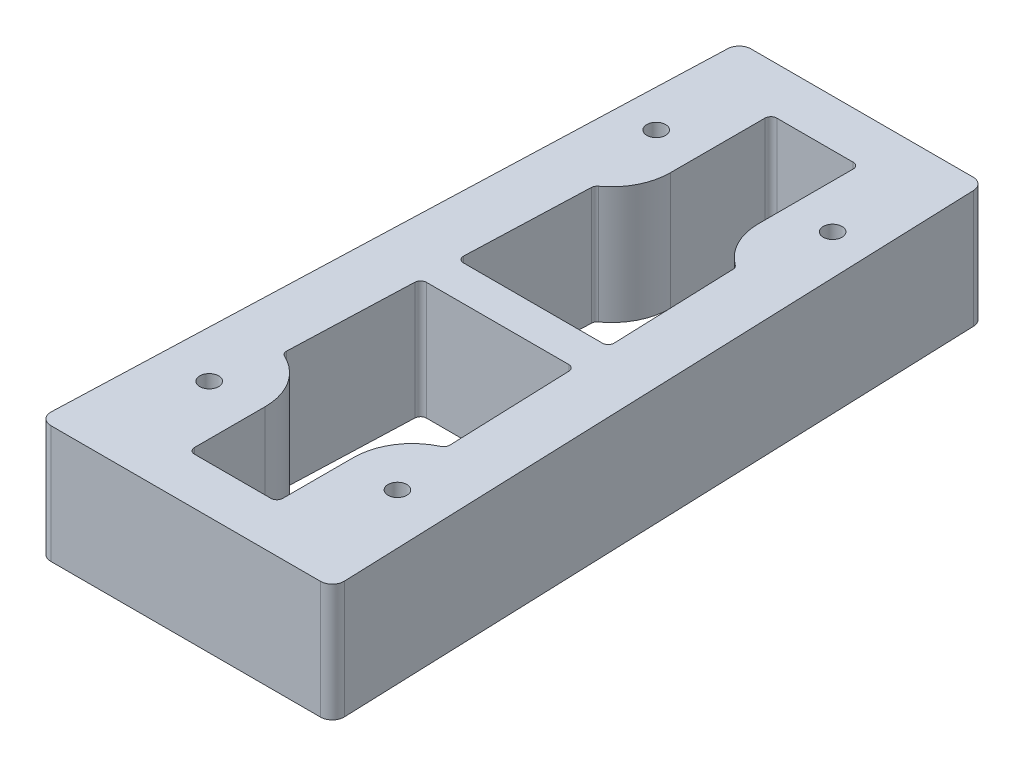
SolidWorks part; units mm, degrees
material "ABS"
ref_plane "前视基准面" through (0, 0, 0) normal (0, 0, 1) x (1, 0, 0)
ref_plane "上视基准面" through (0, 0, 0) normal (0, 1, 0) x (1, 0, 0)
ref_plane "右视基准面" through (0, 0, 0) normal (1, 0, 0) x (0, 0, -1)
other "Configuration Table"
sketch "草图1" plane through (0, 0, 0) normal (0, 1, 0) x (1, 0, 0)
  line L0 (-25, 0) -> (-19, 0)
  line L1 (-19, 165) -> (19, 165)
  line L2 (-19, 165) -> (-19, 0)
  line L3 (-19, 0) -> (19, 0) construction
  line L4 (19, 165) -> (19, 0)
  line L5 (-25, 0) -> (25, 0) construction
  line L6 (-25, 0) -> (-25, -15)
  line L7 (-25, -15) -> (25, -15)
  line L8 (25, 0) -> (25, -15)
  line L9 (19, 0) -> (25, 0)
  line L10 (-19, 156) -> (19, 156) construction
  line L11 (-25, -7.5) -> (25, -7.5) construction
  circle A0 centre (0, -7.5) radius 1.6
  circle A1 centre (20, -7.5) radius 1.6
  circle A2 centre (-20, -7.5) radius 1.6
  circle A3 centre (-15, 156) radius 2.1
  circle A4 centre (15, 156) radius 2.1
  point P8 (22, 0)
  dimension "D7" = 3.2
  dimension "D8" = 3.2
  dimension "D9" = 3.2
  dimension "D12" = 4.2
  dimension "D13" = 4.2
  dimension "D1" = 15
  dimension "D2" = 38
  dimension "D3" = 50
  dimension "D4" = 25
  dimension "D5" = 165
  dimension "D6" = 156
  dimension "D10" = 20
  dimension "D11" = 20
  dimension "D14" = 15
  dimension "D15" = 30
extrude "凸台-拉伸1" add sketch "草图1" along normal blind 20
sketch "草图2" plane through (0, 20, 0) normal (0, 1, 0) x (1, 0, 0)
  line L0 (-19, 165) -> (-25, 0)
  line L1 (-25, 0) -> (-19, 0)
  line L2 (-19, 0) -> (-19, 165)
  line L3 (19, 165) -> (25, 0)
  line L4 (25, 0) -> (19, 0)
  line L5 (19, 0) -> (19, 165)
extrude "凸台-拉伸2" add sketch "草图2" against normal blind 20
sketch "草图3" plane through (0, 20, 0) normal (0, 1, 0) x (1, 0, 0)
  line L0 (-16, 20) -> (16, 20) construction
  line L1 (0, 20) -> (0, 0) construction
  circle A0 centre (16, 20) radius 1.6
  circle A1 centre (-16, 20) radius 1.6
  dimension "D1" = 3.2
  dimension "D2" = 3.2
  dimension "D3" = 32
  dimension "D4" = 20
extrude "切除-拉伸1" cut sketch "草图3" against normal through all
sketch "草图4" plane through (0, 20, 0) normal (0, 1, 0) x (1, 0, 0)
  line L0 (0, 95) -> (0, 0) construction
  line L1 (-15, 95) -> (15, 95) construction
  circle A0 centre (-15, 95) radius 1.6
  circle A1 centre (15, 95) radius 1.6
  dimension "D2" = 3.2
  dimension "D3" = 3.2
  dimension "D1" = 95
  dimension "D4" = 30
extrude "切除-拉伸2" cut sketch "草图4" against normal through all
sketch "草图6" plane through (0, 20, 0) normal (0, 1, 0) x (1, 0, 0)
  line L1 (-25, -15) -> (25, -15)
  line L2 (-25, -15) -> (-25, 0)
  line L3 (-25, 0) -> (25, 0)
  line L4 (25, -15) -> (25, 0)
  line L5 (-39.8866, 115) -> (37.9308, 115)
  line L6 (-39.8866, 115) -> (-39.8866, 196.5424)
  line L7 (-39.8866, 196.5424) -> (37.9308, 196.5424)
  line L8 (37.9308, 115) -> (37.9308, 196.5424)
  point P10 (37.9308, 176.5424)
  dimension "D1" = 115
extrude "切除-拉伸3" cut sketch "草图6" against normal through all
fillet "圆角1" radius 2 4 edges at (-25, 10, 0) (25, 10, 0) (20.8182, 10, -115) (-20.8182, 10, -115)
sketch "草图7" plane through (0, 0, 0) normal (0, -1, 0) x (1, 0, 0)
  line L1 (-13.9025, -30) -> (-12.0116, -82)
  line L3 (12.0116, -82) -> (13.9025, -30)
  line L4 (22.926, 0) -> (-22.926, 0)
  line L5 (-24.9246, -2.0727) -> (-20.8883, -113.0727)
  line L6 (-18.8896, -115) -> (18.8896, -115)
  line L7 (20.8883, -113.0727) -> (24.9246, -2.0727)
  line L8 (22.926, 0) -> (-22.926, 0)
  line L9 (-24.9246, -2.0727) -> (-20.8883, -113.0727)
  line L10 (-18.8896, -115) -> (18.8896, -115)
  line L11 (20.8883, -113.0727) -> (24.9246, -2.0727)
  line L12 (-13.9025, -30) -> (13.9025, -30)
  line L13 (-12.0116, -82) -> (12.0116, -82)
  line L14 (-14.6298, -10) -> (-11.1752, -105) construction
  line L15 (-11.1752, -105) -> (11.1752, -105) construction
  line L16 (11.1752, -105) -> (14.6298, -10) construction
  line L17 (14.6298, -10) -> (-14.6298, -10) construction
  arc A0 (-14.6298, -10) -> (-14.6298, -10) centre (-14.6298, -10) ccw
  arc A1 (-11.1752, -105) -> (-11.1752, -105) centre (-11.1752, -105) ccw
  arc A2 (11.1752, -105) -> (11.1752, -105) centre (11.1752, -105) ccw
  arc A3 (14.6298, -10) -> (14.6298, -10) centre (14.6298, -10) ccw
  arc A4 (-22.926, 0) -> (-24.9246, -2.0727) centre (-22.926, -2) ccw
  arc A5 (-20.8883, -113.0727) -> (-18.8896, -115) centre (-18.8896, -113) ccw
  arc A6 (18.8896, -115) -> (20.8883, -113.0727) centre (18.8896, -113) ccw
  arc A7 (24.9246, -2.0727) -> (22.926, 0) centre (22.926, -2) ccw
  arc A8 (-22.926, 0) -> (-24.9246, -2.0727) centre (-22.926, -2) ccw
  arc A9 (-20.8883, -113.0727) -> (-18.8896, -115) centre (-18.8896, -113) ccw
  arc A10 (18.8896, -115) -> (20.8883, -113.0727) centre (18.8896, -113) ccw
  arc A11 (24.9246, -2.0727) -> (22.926, 0) centre (22.926, -2) ccw
  dimension "D3" = 33
  dimension "D4" = 30
  dimension "D1" = 0
  dimension "D2" = 10
extrude "切除-拉伸4" cut sketch "草图7" against normal through all contours L1 L13 L3 L12
fillet "圆角2" radius 1 4 edges at (-13.9025, 10, -30) (13.9025, 10, -30) (12.0116, 10, -82) (-12.0116, 10, -82)
sketch "草图8" plane through (0, 20, 0) normal (0, 1, 0) x (1, 0, 0)
  line L0 (0, 0) -> (0, 19) construction
  line L1 (-12.8655, 30) -> (12.8655, 30) construction
  line L2 (-7.5, 8) -> (7.5, 8)
  line L3 (-7.5, 8) -> (-7.5, 30)
  line L4 (-7.5, 30) -> (7.5, 30)
  line L5 (7.5, 8) -> (7.5, 30)
  line L6 (-7.5, 8) -> (7.5, 30) construction
  line L7 (-7.5, 30) -> (7.5, 8) construction
  line L8 (22.926, 0) -> (-22.926, 0) construction
  line L9 (0, 115) -> (0, 94.5) construction
  line L10 (-18.8896, 115) -> (18.8896, 115) construction
  line L11 (-11.0473, 82) -> (11.0473, 82) construction
  line L12 (-7.5, 107) -> (7.5, 107)
  line L13 (-7.5, 107) -> (-7.5, 82)
  line L14 (-7.5, 82) -> (7.5, 82)
  line L15 (7.5, 107) -> (7.5, 82)
  line L16 (-7.5, 107) -> (7.5, 82) construction
  line L17 (-7.5, 82) -> (7.5, 107) construction
  dimension "D1" = 8
  dimension "D2" = 15
  dimension "D3" = 15
  dimension "D4" = 8
extrude "切除-拉伸5" cut sketch "草图8" against normal through all
fillet "圆角3" radius 10 4 edges at (7.5, 10, -82) (-7.5, 10, -82) (7.5, 10, -30) (-7.5, 10, -30)
fillet "圆角4" radius 1 4 edges at (7.5, 10, -107) (-7.5, 10, -107) (7.5, 10, -8) (-7.5, 10, -8)
sketch "草图9" plane through (0, 20, 0) normal (0, 1, 0) x (1, 0, 0)
  line L0 (-12.9557, 56.0363) -> (12.9557, 56.0363) construction
  line L1 (-13.8648, 31.0363) -> (-12.0466, 81.0363) construction
  line L2 (12.0466, 81.0363) -> (13.8648, 31.0363) construction
  line L3 (-12.9557, 53.0363) -> (12.9557, 53.0363)
  line L4 (-12.9557, 59.0363) -> (12.9557, 59.0363)
  line L5 (-12.9557, 59.0363) -> (-12.9557, 53.0363)
  line L6 (12.9557, 59.0363) -> (12.9557, 53.0363)
  line L7 (-12.9557, 53.0363) -> (-13.0648, 53.0363)
  line L8 (-13.0648, 53.0363) -> (-12.9557, 59.0363)
  line L9 (12.9557, 53.0363) -> (13.0648, 53.0363)
  line L10 (13.0648, 53.0363) -> (12.9557, 59.0363)
  point P10 (13.0648, 53.0363)
  point P13 (13.0744, 52.7731)
  line M5 (12.0466, 81.0363) -> (13.8648, 31.0363)
  line M15 (-13.8648, 31.0363) -> (-12.0466, 81.0363)
  dimension "D1" = 3
  dimension "D2" = 3
extrude "凸台-拉伸3" add sketch "草图9" against normal up to surface (20 mm away) contours L0 L5 L3 L6 | L6 L9 M5 | L0 L4 M15 M5 | L7 L5 M15 up to face at (0, 0, -56.5216)
fillet "圆角5" radius 1 4 edges at (-13.0648, 10, -53.0363) (13.0648, 10, -53.0363) (12.8466, 10, -59.0363) (-12.8466, 10, -59.0363)
